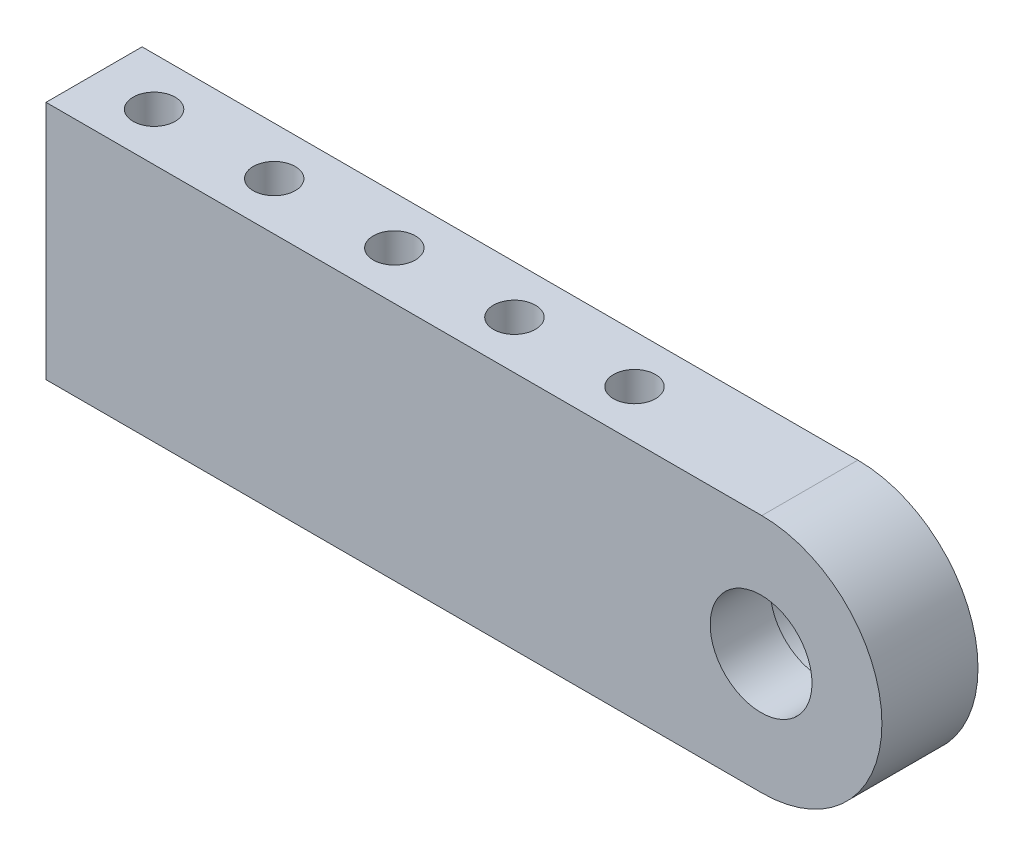
SolidWorks part; units mm, degrees
ref_plane "Plan de face" through (0, 0, 0) normal (0, 0, 1) x (1, 0, 0)
ref_plane "Plan de dessus" through (0, 0, 0) normal (0, 1, 0) x (1, 0, 0)
ref_plane "Plan de droite" through (0, 0, 0) normal (1, 0, 0) x (0, 0, -1)
sketch "Esquisse1" plane through (0, 0, 0) normal (0, 0, 1) x (1, 0, 0)
  line L0 (0, 10) -> (-59.6, 10)
  line L1 (-59.6, 10) -> (-59.6, -10)
  line L2 (-59.6, -10) -> (0, -10)
  circle A0 centre (0, 0) radius 5.3
  arc A1 (0, 10) -> (0, -10) centre (0, 0) cw
  dimension "D1" = 10.6
  dimension "D2" = 20
  dimension "D3" = 59.6
extrude "Boss.-Extru.1" add sketch "Esquisse1" along normal blind 3
sketch "Esquisse2" plane through (0, 0, 3) normal (0, 0, 1) x (1, 0, 0)
  line L13 (-59.6, 10) -> (-59.6, -10)
  line L14 (-59.6, -10) -> (0, -10)
  line L15 (0, 10) -> (-59.6, 10)
  line L16 (-59.6, 10) -> (-59.6, -10)
  line L17 (-59.6, -10) -> (0, -10)
  line L18 (0, 10) -> (-59.6, 10)
  circle A0 centre (-0.0603, 0) radius 4.2397
  circle A2 centre (0, 0) radius 5.3 construction
  arc A7 (0, -10) -> (0, 10) centre (0, 0) ccw
  arc A8 (0, -10) -> (0, 10) centre (0, 0) ccw
  dimension "D1" = 1
  dimension "D2" = 0
extrude "Boss.-Extru.2" add sketch "Esquisse2" along normal blind 5
sketch "Esquisse3" plane through (0, 10, 0) normal (0, 1, 0) x (1, 0, 0)
  line L0 (-59.6, -4) -> (0, -4) construction
  line L1 (-59.6, -8) -> (-59.6, 0) construction
  line L2 (0, -8) -> (0, 0) construction
  line L3 (0, 0) -> (-59.6, 0) construction
  circle A0 centre (-54.6, -4) radius 1.75
  circle A1 centre (-44.6, -4) radius 1.75
  circle A2 centre (-34.6, -4) radius 1.75
  circle A3 centre (-24.6, -4) radius 1.75
  circle A4 centre (-14.6, -4) radius 1.75
  circle A5 centre (-4.6, -4) radius 1.75 construction
  dimension "D2" = 3.5
  dimension "D1" = 4
  dimension "D3" = 5
  dimension "D4" = 6
extrude "Enlèv. mat.-Extru.1" cut sketch "Esquisse3" against normal through all
